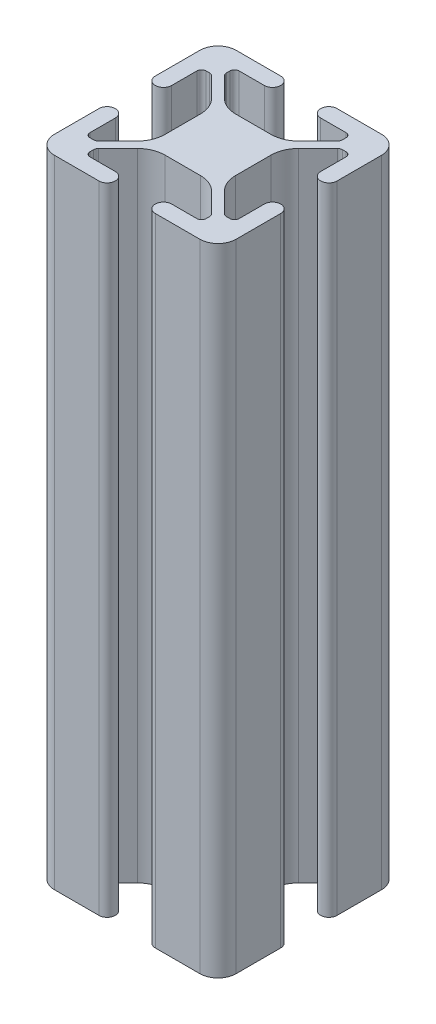
SolidWorks part; units mm, degrees
ref_plane "前视基准面" through (0, 0, 0) normal (0, 0, 1) x (1, 0, 0)
ref_plane "上视基准面" through (0, 0, 0) normal (0, 1, 0) x (1, 0, 0)
ref_plane "右视基准面" through (0, 0, 0) normal (1, 0, 0) x (0, 0, -1)
sketch "草图1" plane through (0, 0, 0) normal (0, 1, 0) x (1, 0, 0)
  line L0 (-1.0428, -10.0859) -> (3.8572, -10.0859)
  line L1 (1.0762, -11.8859) -> (3.8572, -11.8859)
  line L2 (2.8854, -15.3072) -> (0.7226, -13.1443)
  line L3 (2.1786, -16.0141) -> (0.0157, -13.8512)
  line L4 (-3.0428, -12.0859) -> (-3.0428, -16.9859)
  line L5 (-1.2428, -14.2048) -> (-1.2428, -16.9859)
  line L6 (-0.7428, -13.7048) -> (-0.3378, -13.7048)
  line L7 (0.5762, -12.3859) -> (0.5762, -12.7908)
  line L8 (-1.0428, -30.0859) -> (3.8572, -30.0859)
  line L9 (1.0762, -28.2859) -> (3.8572, -28.2859)
  line L10 (2.8854, -24.8645) -> (0.7226, -27.0274)
  line L11 (2.1786, -24.1577) -> (0.0157, -26.3205)
  line L12 (-3.0428, -28.0859) -> (-3.0428, -23.1859)
  line L13 (-1.2428, -25.9669) -> (-1.2428, -23.1859)
  line L14 (-0.7428, -26.4669) -> (-0.3378, -26.4669)
  line L15 (0.5762, -27.7859) -> (0.5762, -27.3809)
  line L16 (14.9572, -10.0859) -> (10.0572, -10.0859)
  line L17 (12.8383, -11.8859) -> (10.0572, -11.8859)
  line L18 (11.029, -15.3072) -> (13.1919, -13.1443)
  line L19 (11.7359, -16.0141) -> (13.8988, -13.8512)
  line L20 (16.9572, -12.0859) -> (16.9572, -16.9859)
  line L21 (15.1572, -14.2048) -> (15.1572, -16.9859)
  line L22 (14.6572, -13.7048) -> (14.2523, -13.7048)
  line L23 (13.3383, -12.3859) -> (13.3383, -12.7908)
  line L24 (14.9572, -30.0859) -> (10.0572, -30.0859)
  line L25 (12.8383, -28.2859) -> (10.0572, -28.2859)
  line L26 (11.029, -24.8645) -> (13.1919, -27.0274)
  line L27 (11.7359, -24.1577) -> (13.8988, -26.3205)
  line L28 (16.9572, -28.0859) -> (16.9572, -23.1859)
  line L29 (15.1572, -25.9669) -> (15.1572, -23.1859)
  line L30 (14.6572, -26.4669) -> (14.2523, -26.4669)
  line L31 (13.3383, -27.7859) -> (13.3383, -27.3809)
  line L32 (5.0068, -16.1859) -> (8.9077, -16.1859)
  line L33 (10.8572, -18.1354) -> (10.8572, -22.0363)
  line L34 (3.0572, -18.1354) -> (3.0572, -22.0363)
  line L35 (5.0068, -23.9859) -> (8.9077, -23.9859)
  circle A0 centre (6.9572, -20.0859) radius 2.5
  arc A1 (2.8854, -15.3072) -> (5.0068, -16.1859) centre (5.0068, -13.1859) ccw
  arc A2 (3.0572, -18.1354) -> (2.1786, -16.0141) centre (0.0572, -18.1354) ccw
  arc A3 (3.8572, -11.8859) -> (3.8572, -10.0859) centre (3.8572, -10.9859) ccw
  arc A4 (0.5762, -12.7908) -> (0.7226, -13.1443) centre (1.0762, -12.7908) ccw
  arc A5 (0.0157, -13.8512) -> (-0.3378, -13.7048) centre (-0.3378, -14.2048) ccw
  arc A6 (-3.0428, -16.9859) -> (-1.2428, -16.9859) centre (-2.1428, -16.9859) ccw
  arc A7 (-1.0428, -10.0859) -> (-3.0428, -12.0859) centre (-1.0428, -12.0859) ccw
  arc A8 (-0.7428, -13.7048) -> (-1.2428, -14.2048) centre (-0.7428, -14.2048) ccw
  arc A9 (1.0762, -11.8859) -> (0.5762, -12.3859) centre (1.0762, -12.3859) ccw
  arc A10 (5.0068, -23.9859) -> (2.8854, -24.8645) centre (5.0068, -26.9859) ccw
  arc A11 (2.1786, -24.1577) -> (3.0572, -22.0363) centre (0.0572, -22.0363) ccw
  arc A12 (3.8572, -30.0859) -> (3.8572, -28.2859) centre (3.8572, -29.1859) ccw
  arc A13 (0.7226, -27.0274) -> (0.5762, -27.3809) centre (1.0762, -27.3809) ccw
  arc A14 (-0.3378, -26.4669) -> (0.0157, -26.3205) centre (-0.3378, -25.9669) ccw
  arc A15 (-1.2428, -23.1859) -> (-3.0428, -23.1859) centre (-2.1428, -23.1859) ccw
  arc A16 (-3.0428, -28.0859) -> (-1.0428, -30.0859) centre (-1.0428, -28.0859) ccw
  arc A17 (-1.2428, -25.9669) -> (-0.7428, -26.4669) centre (-0.7428, -25.9669) ccw
  arc A18 (0.5762, -27.7859) -> (1.0762, -28.2859) centre (1.0762, -27.7859) ccw
  arc A19 (8.9077, -16.1859) -> (11.029, -15.3072) centre (8.9077, -13.1859) ccw
  arc A20 (11.7359, -16.0141) -> (10.8572, -18.1354) centre (13.8572, -18.1354) ccw
  arc A21 (10.0572, -10.0859) -> (10.0572, -11.8859) centre (10.0572, -10.9859) ccw
  arc A22 (13.1919, -13.1443) -> (13.3383, -12.7908) centre (12.8383, -12.7908) ccw
  arc A23 (14.2523, -13.7048) -> (13.8988, -13.8512) centre (14.2523, -14.2048) ccw
  arc A24 (15.1572, -16.9859) -> (16.9572, -16.9859) centre (16.0572, -16.9859) ccw
  arc A25 (16.9572, -12.0859) -> (14.9572, -10.0859) centre (14.9572, -12.0859) ccw
  arc A26 (15.1572, -14.2048) -> (14.6572, -13.7048) centre (14.6572, -14.2048) ccw
  arc A27 (13.3383, -12.3859) -> (12.8383, -11.8859) centre (12.8383, -12.3859) ccw
  arc A28 (11.029, -24.8645) -> (8.9077, -23.9859) centre (8.9077, -26.9859) ccw
  arc A29 (10.8572, -22.0363) -> (11.7359, -24.1577) centre (13.8572, -22.0363) ccw
  arc A30 (10.0572, -28.2859) -> (10.0572, -30.0859) centre (10.0572, -29.1859) ccw
  arc A31 (13.3383, -27.3809) -> (13.1919, -27.0274) centre (12.8383, -27.3809) ccw
  arc A32 (13.8988, -26.3205) -> (14.2523, -26.4669) centre (14.2523, -25.9669) ccw
  arc A33 (16.9572, -23.1859) -> (15.1572, -23.1859) centre (16.0572, -23.1859) ccw
  arc A34 (14.9572, -30.0859) -> (16.9572, -28.0859) centre (14.9572, -28.0859) ccw
  arc A35 (14.6572, -26.4669) -> (15.1572, -25.9669) centre (14.6572, -25.9669) ccw
  arc A36 (12.8383, -28.2859) -> (13.3383, -27.7859) centre (12.8383, -27.7859) ccw
extrude "凸台-拉伸1" add sketch "草图1" along normal blind 70 contours L32 A19 L18 A22 L23 A27 L17 A21 L16 A25 L20 A24 L21 A26 L22 A23 L19 A20 L33 A29 L27 A32 L30 A35 L29 A33 L28 A34 L24 A30 L25 A36 L31 A31 L26 A28 L35 A10 L10 A13 L15 A18 L9 A12 L8 A16 L12 A15 L13 A17 L14 A14 L11 A11 L34 A2 L3 A5 L6 A8 L5 A6 L4 A7 L0 A3 L1 A9 L7 A4 L2 A1
ref_plane "基准面1" through (0, 35, 0) normal (0, 1, 0) x (1, 0, 0)
ref_plane "基准面2" through (6.9572, 0, 0) normal (-1, 0, 0) x (0, 0, 1)
